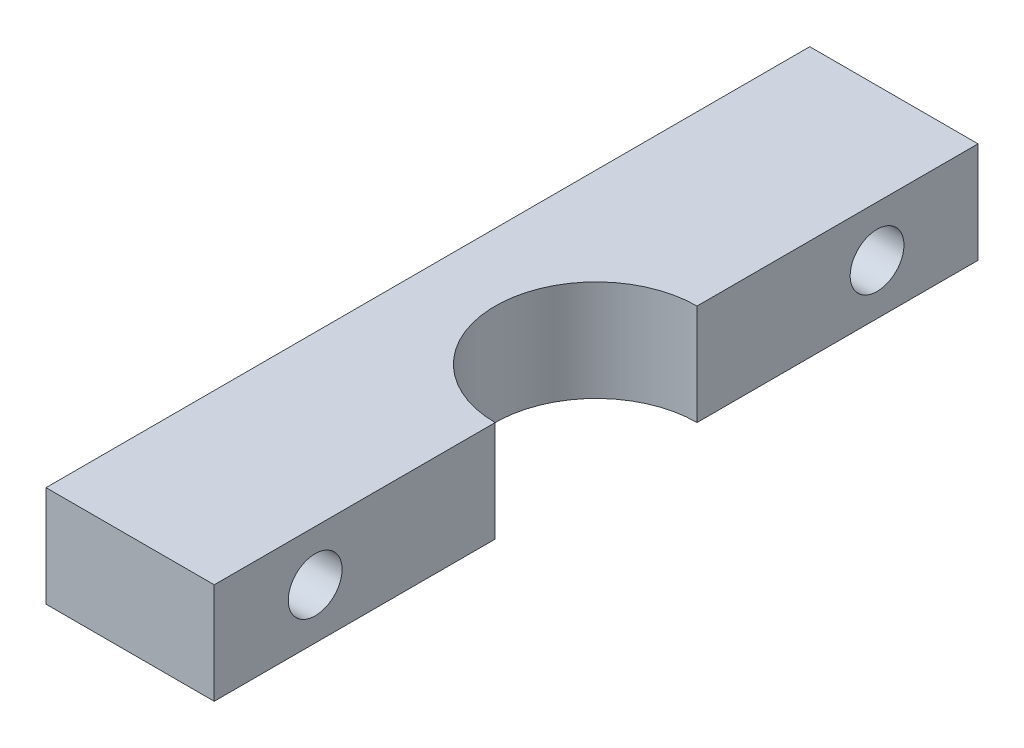
SolidWorks part; units mm, degrees
ref_plane "Płaszczyzna przednia" through (0, 0, 0) normal (0, 0, 1) x (1, 0, 0)
ref_plane "Płaszczyzna górna" through (0, 0, 0) normal (0, 1, 0) x (1, 0, 0)
ref_plane "Płaszczyzna prawa" through (0, 0, 0) normal (1, 0, 0) x (0, 0, -1)
sketch "Sketch1" plane through (0, 0, 0) normal (0, 1, 0) x (1, 0, 0)
  line L0 (10, 28.7) -> (10, 45.4)
  line L1 (0, 0) -> (10, 0)
  line L2 (0, 0) -> (0, 45.4)
  line L3 (0, 45.4) -> (10, 45.4)
  line L4 (10, 0) -> (10, 16.7)
  line L5 (0, 0) -> (10, 45.4) construction
  line L6 (0, 45.4) -> (10, 0) construction
  line L7 (-4.8209, 22.7) -> (14.8209, 22.7) construction
  line L8 (10, 0) -> (10, 45.4) construction
  arc A0 (10, 28.7) -> (10, 16.7) centre (10, 22.7) ccw
  point P4 (5, 22.7)
  point P12 (5, 22.7)
  dimension "D3" = 12
  dimension "D1" = 45.4
  dimension "D2" = 10
extrude "Boss-Extrude1" add sketch "Sketch1" along normal blind 6
hole_wizard "Ø3.2 (3.2) Diameter Hole1" positions "Sketch2" profile "Sketch3" hole size "Ø3.2" standard "ANSI Metric" end condition through all
sketch "Sketch2" plane through (0, 0, 0) normal (-1, 0, 0) x (0, 0, 1)
  line L0 (0, 6) -> (0, 0) construction
  line L2 (-45.4, 6) -> (0, 6) construction
  line L3 (-45.4, 6) -> (-45.4, 0) construction
  point P0 (-6, 3)
  point P2 (-39.4, 3)
  dimension "D1" = 6
  dimension "D2" = 3
  dimension "D3" = 6
sketch "Sketch3" plane through (0, 3, -6) normal (0, 1, 0) x (0, 0, 1)
  line L0 (0, 0) -> (0, 10)
  line L1 (0, 10) -> (1.6, 10)
  line L2 (1.6, 10) -> (1.6, 0)
  line L5 (1.6, 0) -> (0, 0)
  line L11 (0, -6.35) -> (0, 107.95) construction
  dimension "Thru Hole Dia." = 3.2
  dimension "Thru Hole Depth" = 10
